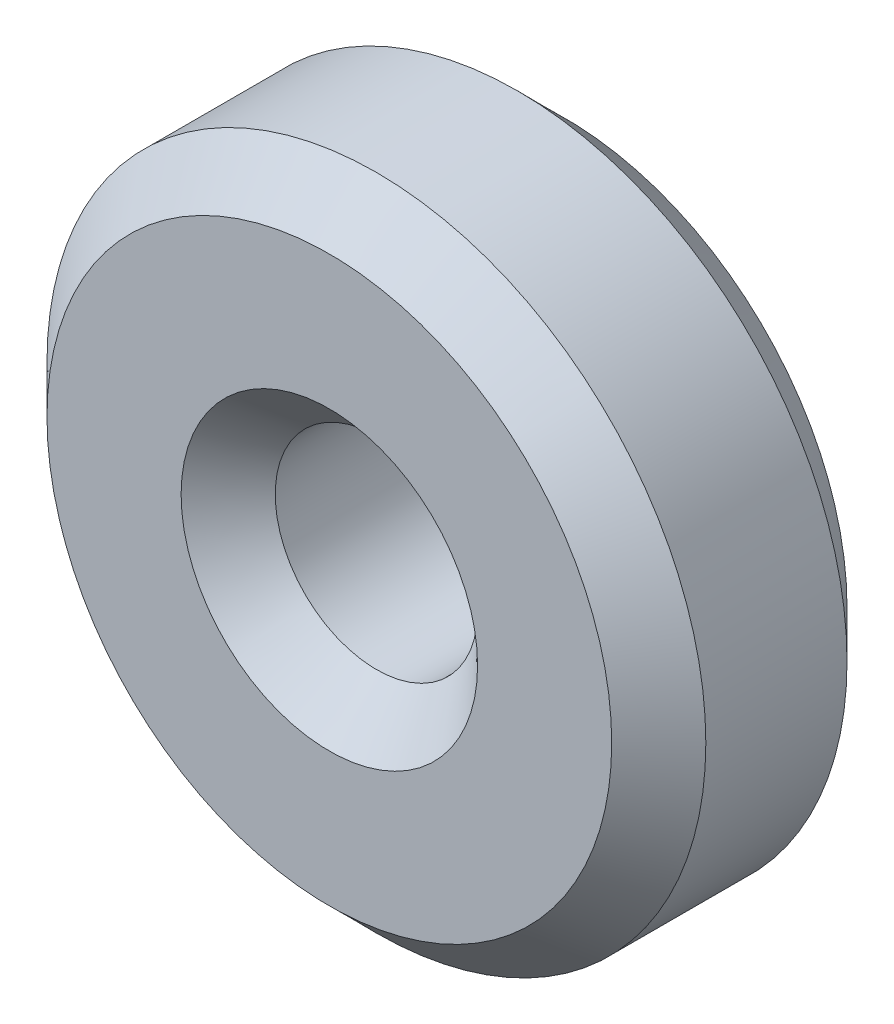
SolidWorks part; units mm, degrees
material "ABS"
ref_plane "Front" through (0, 0, 0) normal (0, 0, 1) x (1, 0, 0)
ref_plane "Top" through (0, 0, 0) normal (0, 1, 0) x (1, 0, 0)
ref_plane "Right" through (0, 0, 0) normal (1, 0, 0) x (0, 0, -1)
sketch "Эскиз1" plane through (0, 0, 0) normal (0, 0, 1) x (1, 0, 0)
  circle A0 centre (0, 0) radius 7
  circle A1 centre (0, 0) radius 2.15
  dimension "D1" = 14
  dimension "D2" = 4.3
extrude "Бобышка-Вытянуть1" add sketch "Эскиз1" along normal blind 5
chamfer "Фаска1" distance 1 angle 45 4 edges at (2.15, 0, 0) (2.15, 0, 5) (7, 0, 5) (7, 0, 0)
